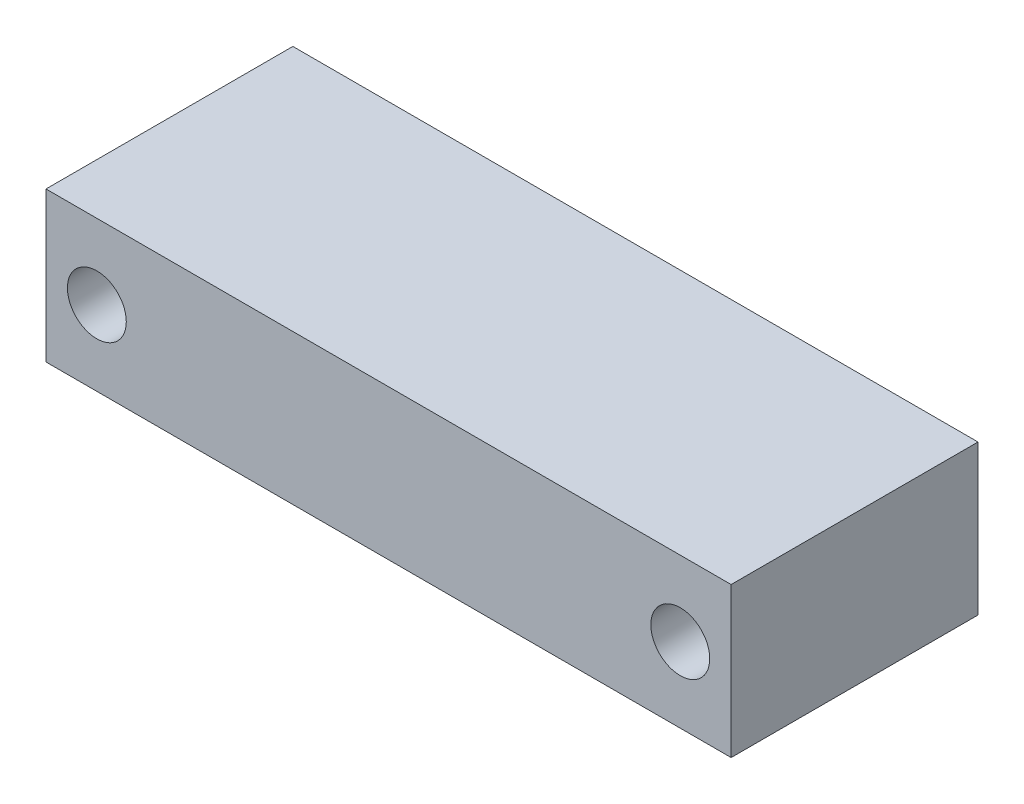
SolidWorks part; units mm, degrees
ref_plane "前视基准面" through (0, 0, 0) normal (0, 0, 1) x (1, 0, 0)
ref_plane "上视基准面" through (0, 0, 0) normal (0, 1, 0) x (1, 0, 0)
ref_plane "右视基准面" through (0, 0, 0) normal (1, 0, 0) x (0, 0, -1)
sketch "草图1" plane through (0, 0, 0) normal (0, 0, 1) x (1, 0, 0)
  line L1 (-32, -7) -> (32, -7)
  line L2 (-32, -7) -> (-32, 7)
  line L3 (-32, 7) -> (32, 7)
  line L4 (32, -7) -> (32, 7)
  line L5 (-32, -7) -> (32, 7) construction
  line L6 (-32, 7) -> (32, -7) construction
  circle A0 centre (-27.25, 0) radius 2.75
  circle A1 centre (27.25, 0) radius 2.75
  point P0 (0, 0)
  dimension "D3" = 5.5
  dimension "D4" = 5.5
  dimension "D5" = 4.75
  dimension "D6" = 4.75
  dimension "D1" = 64
  dimension "D2" = 14
extrude "凸台-拉伸1" add sketch "草图1" along normal blind 23.06
